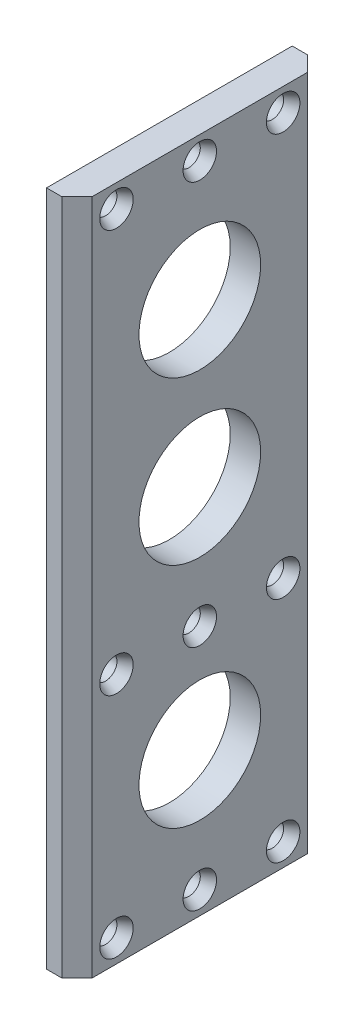
SolidWorks part; units mm, degrees
ref_plane "Front Plane" through (0, 0, 0) normal (0, 0, 1) x (1, 0, 0)
ref_plane "Top Plane" through (0, 0, 0) normal (0, 1, 0) x (1, 0, 0)
ref_plane "Right Plane" through (0, 0, 0) normal (1, 0, 0) x (0, 0, -1)
sketch "Sketch1" plane through (0, 0, 0) normal (1, 0, 0) x (0, 0, -1)
  line L1 (0.0252, 0) -> (32.3385, 0)
  line L2 (0.0252, 0) -> (0.0252, -89)
  line L3 (0.0252, -89) -> (32.3385, -89)
  line L4 (32.3385, 0) -> (32.3385, -89)
extrude "Extrude1" add sketch "Sketch1" along normal blind 4
sketch "Sketch2" plane through (4, 0, 0) normal (1, 0, 0) x (0, 0, -1)
  line L0 (5.2196, 0) -> (5.2196, -6) construction
  line L1 (16.1819, 0) -> (16.1819, 9.2123) construction
  line L3 (32.3385, -44.5) -> (66.1259, -44.5) construction
  line L5 (37.3889, -56) -> (48.267, -56) construction
  line L7 (5.2196, -86) -> (5.2196, -94.7661) construction
  line L8 (27.1441, -86) -> (27.1441, -69.676) construction
  circle A0 centre (5.2196, -3) radius 1.5
  circle A1 centre (27.1441, -3) radius 1.5
  circle A2 centre (16.1819, -3) radius 1.5
  circle A3 centre (27.1441, -86) radius 1.5
  circle A4 centre (16.1819, -86) radius 1.5
  circle A5 centre (5.2196, -86) radius 1.5
  circle A6 centre (5.2196, -56) radius 1.5
  circle A7 centre (16.1819, -56) radius 1.5
  circle A8 centre (27.1441, -56) radius 1.5
  circle A9 centre (16.1819, -18.8147) radius 8
  circle A10 centre (16.1819, -40.1499) radius 8
  circle A11 centre (16.1819, -70.1169) radius 8
extrude "Cut-Extrude1" cut sketch "Sketch2" against normal blind 4
chamfer "Chamfer1" distance 2 angle 45 2 edges at (4, -44.5, -0.0252) (4, -44.5, -32.3385)
sketch "Sketch4" plane through (4, 0, 0) normal (1, 0, 0) x (0, 0, -1)
  circle A0 centre (5.2196, -3) radius 2.2
  circle A1 centre (16.1819, -3) radius 2.2
  circle A2 centre (27.1441, -3) radius 2.2
  circle A3 centre (5.2196, -56) radius 2.2
  circle A4 centre (16.1819, -56) radius 2.2
  circle A5 centre (27.1441, -56) radius 2.2
  circle A6 centre (5.2196, -86) radius 2.2
  circle A7 centre (16.1819, -86) radius 2.2
  circle A8 centre (27.1441, -86) radius 2.2
extrude "Cut-Extrude2" cut sketch "Sketch4" against normal blind 1.5 draft 26
